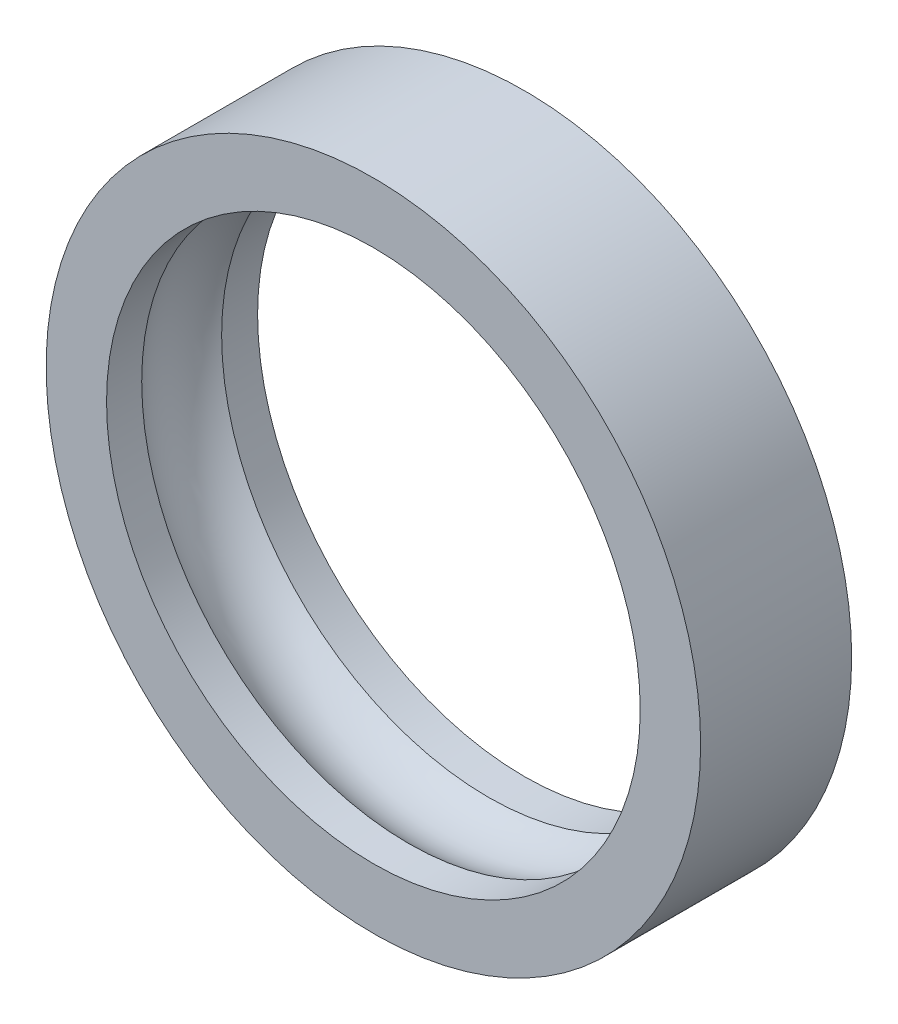
SolidWorks part; units mm, degrees
ref_plane "Front Plane" through (0, 0, 0) normal (0, 0, 1) x (1, 0, 0)
ref_plane "Top Plane" through (0, 0, 0) normal (0, 1, 0) x (1, 0, 0)
ref_plane "Right Plane" through (0, 0, 0) normal (1, 0, 0) x (0, 0, -1)
sketch "Sketch1" plane through (0, 0, 0) normal (1, 0, 0) x (0, 0, -1)
  line L0 (0, 0) -> (0, 59) construction
  line L3 (15, 53) -> (15, 65)
  line L4 (15, 65) -> (-15, 65)
  line L5 (-15, 53) -> (-15, 65)
  line L6 (15, 53) -> (-15, 65) construction
  line L7 (15, 65) -> (-15, 53) construction
  line L8 (0, 0) -> (61.5511, 0) construction
  line L9 (-15, 53) -> (-8.0186, 53)
  line L10 (7.856, 53) -> (15, 53)
  arc A1 (7.856, 53) -> (-8.0186, 53) centre (-0.0813, 44) ccw
  point P10 (-0.0813, 56)
  point P12 (61.5511, 0)
  dimension "D3" = 12
  dimension "D1" = 65
  dimension "D2" = 53
  dimension "30" = 30
  dimension "D4" = 3
revolve "Revolve6" add sketch "Sketch1" angle 360 about L8
